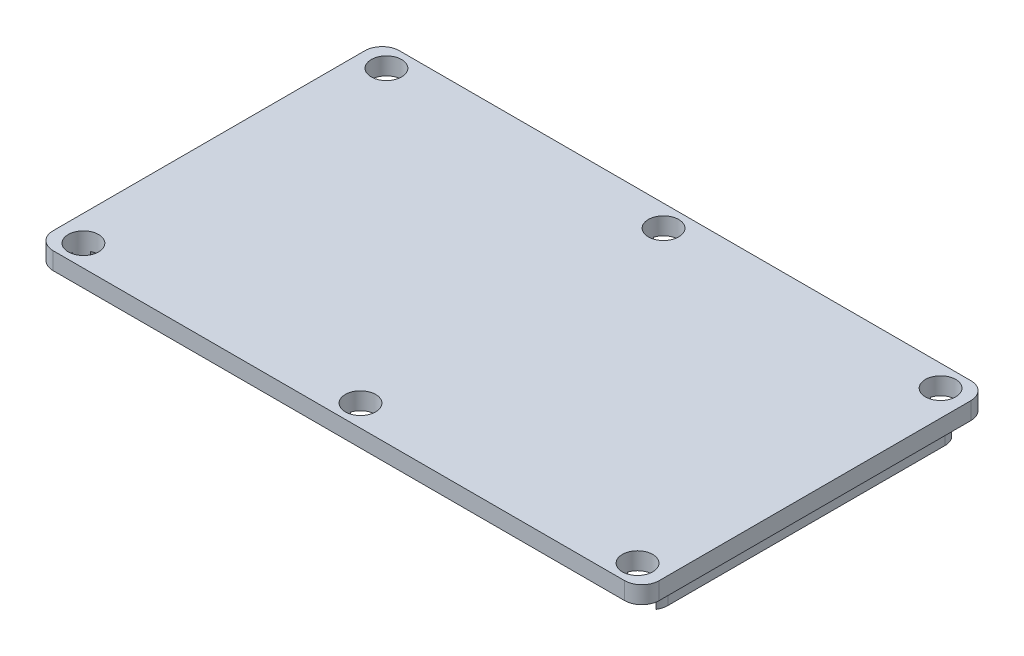
SolidWorks part; units mm, degrees
material "AISI 304"
ref_plane "Front Plane" through (0, 0, 0) normal (0, 0, 1) x (1, 0, 0)
ref_plane "Top Plane" through (0, 0, 0) normal (0, 1, 0) x (1, 0, 0)
ref_plane "Right Plane" through (0, 0, 0) normal (1, 0, 0) x (0, 0, -1)
sketch "Sketch1" plane through (0, 0, 0) normal (0, 1, 0) x (1, 0, 0)
  line L1 (-33, -20) -> (33, -20)
  line L2 (-35, -18) -> (-35, 18)
  line L3 (-33, 20) -> (33, 20)
  line L4 (35, -18) -> (35, 18)
  line L5 (-35, -20) -> (35, 20) construction
  line L6 (-35, 20) -> (35, -20) construction
  arc A0 (33, -20) -> (35, -18) centre (33, -18) ccw
  arc A1 (33, 20) -> (35, 18) centre (33, 18) cw
  arc A2 (-33, -20) -> (-35, -18) centre (-33, -18) cw
  arc A3 (-35, 18) -> (-33, 20) centre (-33, 18) cw
  point P0 (0, 0)
  dimension "D3" = 2
  dimension "D1" = 70
  dimension "D2" = 40
extrude "Boss-Extrude1" add sketch "Sketch1" along normal blind 2
sketch "Sketch2" plane through (0, 0, 0) normal (0, -1, 0) x (1, 0, 0)
  line L0 (-35, -18) -> (-35, 18) construction
  line L1 (-32, 18) -> (32, 18)
  line L2 (-34, 16) -> (-34, -16)
  line L3 (-32, -18) -> (32, -18)
  line L4 (34, 16) -> (34, -16)
  line L5 (-33, 20) -> (33, 20) construction
  line L6 (35, 18) -> (35, -18) construction
  line L7 (33, -20) -> (-33, -20) construction
  line L8 (-31, 17) -> (31, 17)
  line L9 (33, 15) -> (33, -15)
  line L10 (-31, -17) -> (31, -17)
  line L11 (-33, 15) -> (-33, -15)
  line L12 (-34, 18) -> (34, 18) construction
  line L13 (34, 18) -> (34, -18) construction
  line L14 (-33, 17) -> (33, 17) construction
  line L15 (33, 17) -> (33, -17) construction
  line L16 (-33, -17) -> (33, -17) construction
  line L17 (-34, -18) -> (34, -18) construction
  line L18 (-33, 17) -> (-33, -17) construction
  line L19 (-34, 18) -> (-34, -18) construction
  arc A0 (32, 18) -> (34, 16) centre (32, 16) cw
  arc A1 (31, 17) -> (33, 15) centre (31, 15) cw
  arc A2 (33, -15) -> (31, -17) centre (31, -15) cw
  arc A3 (32, -18) -> (34, -16) centre (32, -16) ccw
  arc A4 (-31, -17) -> (-33, -15) centre (-31, -15) cw
  arc A5 (-34, -16) -> (-32, -18) centre (-32, -16) ccw
  arc A6 (-31, 17) -> (-33, 15) centre (-31, 15) ccw
  arc A7 (-32, 18) -> (-34, 16) centre (-32, 16) ccw
  dimension "D6" = 2
  dimension "D1" = 1
  dimension "D2" = 2
  dimension "D3" = 1
  dimension "D4" = 2
  dimension "D5" = 1
extrude "Boss-Extrude2" add sketch "Sketch2" along normal blind 2
sketch "Sketch3" plane through (0, 2, 0) normal (0, 1, 0) x (1, 0, 0)
  circle A0 centre (-32, 17.5) radius 1.75
  circle A1 centre (0, 17.5) radius 1.75
  circle A2 centre (32, 17.5) radius 1.75
  circle A3 centre (32, -17.5) radius 1.75
  circle A4 centre (0, -17.5) radius 1.75
  circle A5 centre (-32, -17.5) radius 1.75
  dimension "D1" = 17.5
  dimension "D2" = 17.5
  dimension "D3" = 32
  dimension "D4" = 32
  dimension "D5" = 3.5
extrude "Cut-Extrude1" cut sketch "Sketch3" against normal blind 10
